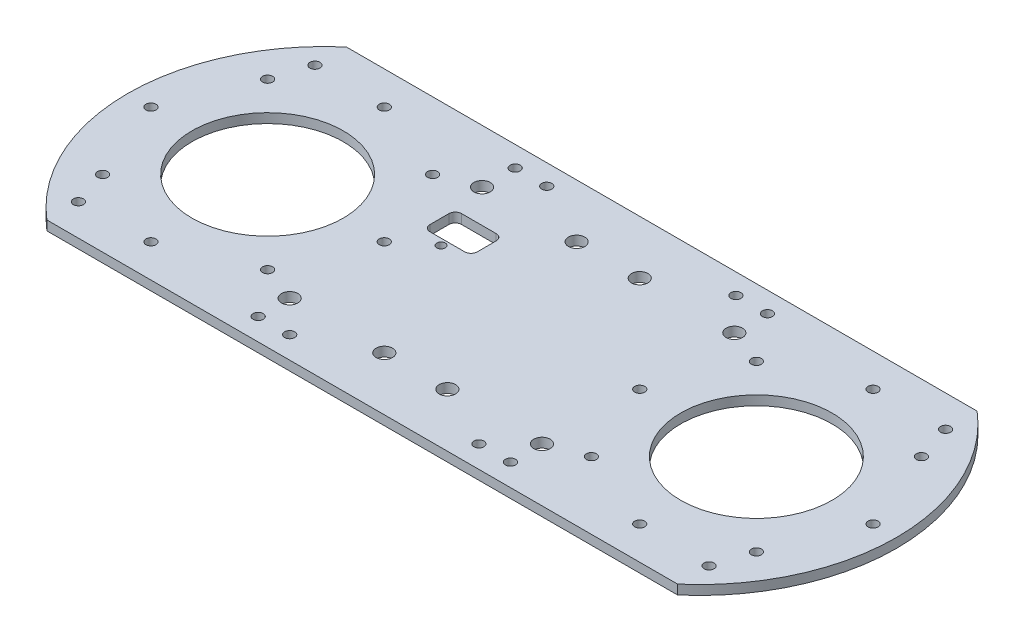
SolidWorks part; units mm, degrees
material "6061 合金"
ref_plane "前视基准面" through (0, 0, 0) normal (0, 0, 1) x (1, 0, 0)
ref_plane "上视基准面" through (0, 0, 0) normal (0, 1, 0) x (1, 0, 0)
ref_plane "右视基准面" through (0, 0, 0) normal (1, 0, 0) x (0, 0, -1)
sketch "草图1" plane through (0, 0, 0) normal (0, 1, 0) x (1, 0, 0)
  line L0 (100, 0) -> (-100, 0) construction
  line L1 (100, -47.5) -> (-100, -47.5)
  line L2 (100, 47.5) -> (-100, 47.5)
  line L3 (77.5, 0) -> (103.663, 26.163) construction
  line L4 (77.5, 0) -> (114.5, 0) construction
  line L5 (77.5, 0) -> (77.5, -37) construction
  line L6 (0, 0) -> (0, -47.5) construction
  line L7 (100, 47.5) -> (100, -47.5) construction
  line L8 (-36, 20) -> (-25, 20)
  line L9 (-38, 18) -> (-38, 12)
  line L10 (-36, 10) -> (-25, 10)
  line L11 (-23, 18) -> (-23, 12)
  line L12 (-30.5, 20) -> (-30.5, 10) construction
  arc A0 (100, -47.5) -> (100, 47.5) centre (100, 0) ccw
  arc A1 (-100, 47.5) -> (-100, -47.5) centre (-100, 0) ccw
  circle A2 centre (77.5, 0) radius 18
  circle A3 centre (77.5, 0) radius 37 construction
  circle A4 centre (77.5, 37) radius 1.6
  circle A5 centre (103.663, 26.163) radius 1.6
  circle A6 centre (114.5, 0) radius 1.6
  circle A7 centre (103.663, -26.163) radius 1.6
  circle A8 centre (77.5, -37) radius 1.6
  circle A9 centre (51.337, -26.163) radius 1.6
  circle A10 centre (40.5, 0) radius 1.6
  circle A11 centre (51.337, 26.163) radius 1.6
  circle A12 centre (-51.337, 26.163) radius 1.6
  circle A13 centre (-40.5, 0) radius 1.6
  circle A14 centre (-51.337, -26.163) radius 1.6
  circle A15 centre (-77.5, -37) radius 1.6
  circle A16 centre (-103.663, -26.163) radius 1.6
  circle A17 centre (-114.5, 0) radius 1.6
  circle A18 centre (-103.663, 26.163) radius 1.6
  circle A19 centre (-77.5, 37) radius 1.6
  circle A20 centre (-77.5, 0) radius 18
  circle A21 centre (-10, -30.5) radius 2.6
  circle A22 centre (10, -30.5) radius 2.6
  circle A23 centre (-40, -30.5) radius 2.6
  circle A24 centre (40, -30.5) radius 2.6
  circle A25 centre (40, 30.5) radius 2.6
  circle A26 centre (10, 30.5) radius 2.6
  circle A27 centre (-10, 30.5) radius 2.6
  circle A28 centre (-40, 30.5) radius 2.6
  circle A29 centre (-30, -40.5) radius 1.6
  circle A30 centre (-40, -40.5) radius 1.6
  circle A31 centre (40, -40.5) radius 1.6
  circle A32 centre (30, -40.5) radius 1.6
  arc A37 (100, 47.5) -> (100, -47.5) centre (100, 0) cw
  arc A38 (100, -47.5) -> (100, 47.5) centre (59.5, 0) ccw
  arc A39 (-100, -47.5) -> (-100, 47.5) centre (-59.5, 0) cw
  circle A40 centre (-40, 41) radius 1.6
  circle A41 centre (-30, 41) radius 1.6
  circle A42 centre (30, 41) radius 1.6
  circle A43 centre (40, 41) radius 1.6
  arc A44 (-38, 12) -> (-36, 10) centre (-36, 12) ccw
  arc A45 (-25, 10) -> (-23, 12) centre (-25, 12) ccw
  arc A46 (-25, 20) -> (-23, 18) centre (-25, 18) cw
  arc A47 (-36, 20) -> (-38, 18) centre (-36, 18) ccw
  circle A48 centre (100, 37.5) radius 1.6
  circle A49 centre (100, -37.5) radius 1.6
  circle A50 centre (-100, -37.5) radius 1.6
  circle A51 centre (-100, 37.5) radius 1.6
  circle A52 centre (-30.5, 8) radius 1.35
  point P2 (0, 0)
  point P92 (-38, 10)
  point P97 (-23, 20)
  point P100 (-38, 20)
  dimension "D1" = 36
  dimension "D3" = 3.2
  dimension "D4" = 3.2
  dimension "D5" = 3.2
  dimension "D7" = 5.2
  dimension "D9" = 10
  dimension "D11" = 3.2
  dimension "D12" = 30
  dimension "D13" = 7
  dimension "D15" = 77.5
  dimension "D16" = 2
  dimension "D19" = 2
  dimension "D22" = 3.2
  dimension "D23" = 0
  dimension "D24" = 10
  dimension "D25" = 2.7
  dimension "D26" = 2
  dimension "D2" = 95
  dimension "D6" = 200
  dimension "D8" = 17
  dimension "D17" = 10
  dimension "D18" = 15
  dimension "D20" = 10
  dimension "D21" = 23
  dimension "D10" = 2
  dimension "D14" = 2
extrude "凸台-拉伸1" add sketch "草图1" along normal blind 3
sketch "草图2" plane through (0, 3, 0) normal (0, 1, 0) x (1, 0, 0)
  line L0 (0, 47.5) -> (0, -47.5) construction
  line L1 (100, 47.5) -> (-100, 47.5) construction
  line L2 (100, -47.5) -> (-100, -47.5) construction
  circle A0 centre (77.5, 0) radius 24
  circle A1 centre (-77.5, 0) radius 24
  dimension "D1" = 48
extrude "切除-拉伸1" cut sketch "草图2" against normal up to next
